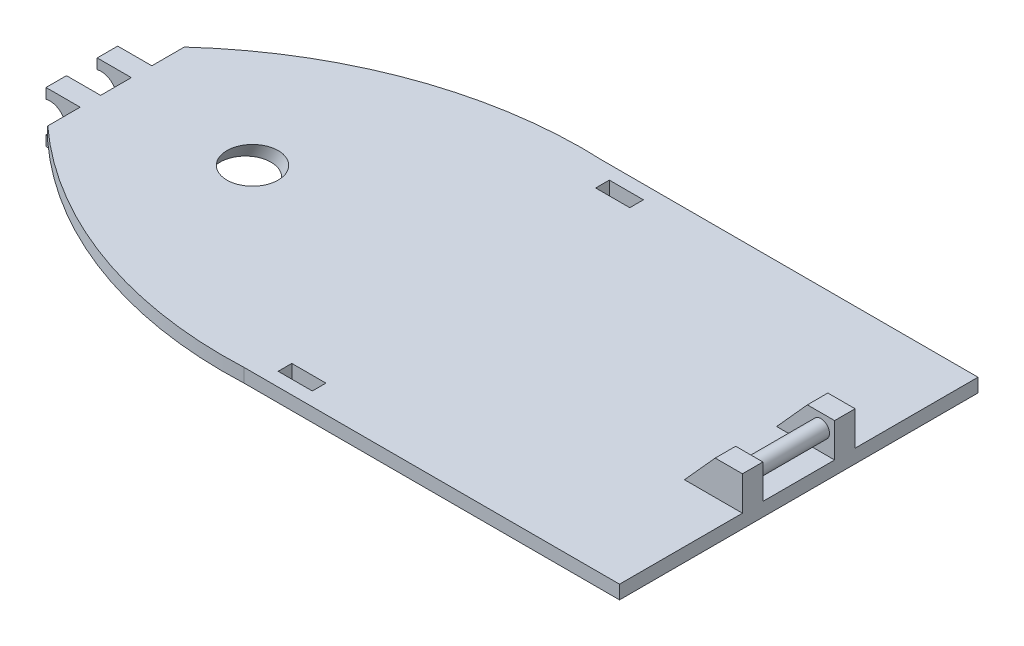
SolidWorks part; units mm, degrees
ref_plane "Front Plane" through (0, 0, 0) normal (0, 0, 1) x (1, 0, 0)
ref_plane "Top Plane" through (0, 0, 0) normal (0, 1, 0) x (1, 0, 0)
ref_plane "Right Plane" through (0, 0, 0) normal (1, 0, 0) x (0, 0, -1)
sketch "Sketch1" plane through (0, 0, 0) normal (0, 1, 0) x (1, 0, 0)
  line L0 (-110, 0) -> (0, 0)
  line L1 (0, 0) -> (0, -105)
  line L2 (0, -105) -> (-110, -105)
  line L4 (-200, -72.5) -> (-200, -32.5)
  arc A2 (-200, -32.5) -> (-110, 0) centre (-115.7774, -124.8664) cw
  arc A3 (-200, -72.5) -> (-110, -105) centre (-115.7774, 19.8664) ccw
  point P11 (-200, -52.5)
  point P12 (0, -52.5)
  dimension "D4" = 40
  dimension "D6" = 125
  dimension "D7" = 125
  dimension "D1" = 110
  dimension "D2" = 105
  dimension "D3" = 200
  dimension "D5" = 110
extrude "Boss-Extrude1" add sketch "Sketch1" along normal blind 4
sketch "Sketch2" plane through (0, 0, 105) normal (0, 0, 1) x (1, 0, 0)
  line L0 (-200, 4) -> (-210, 4)
  line L1 (-188, 0) -> (-200, -11)
  line L2 (57.8969, 0) -> (-57.8969, 0) construction
  line L3 (-200, -11) -> (-210, -11)
  line L4 (-210, 4) -> (-210, 1)
  line L5 (-210, -11) -> (-210, -8)
  line L6 (-200, 4) -> (-188, 0)
  arc A0 (-210, 1) -> (-210, -8) centre (-208.8457, -3.5) cw
  point P11 (-204.2, -3.5)
  dimension "D8" = 4.6457
  dimension "D1" = 10
  dimension "D2" = 15
  dimension "D3" = 3
  dimension "D4" = 3
  dimension "D5" = 10
  dimension "D6" = 5.8
  dimension "D7" = 22
extrude "Boss-Extrude2" add sketch "Sketch2" along normal mid plane 6 from offset 45 offset against normal yes
ref_plane "Plane1" through (0, 0, 52.5) normal (0, 0, 1) x (1, 0, 0)
mirror "Mirror1" about plane through (0, 0, 52.5) normal (0, 0, 1) of "Boss-Extrude2"
ref_plane "Plane2" through (-100, 0, 0) normal (1, 0, 0) x (0, 0, -1)
sketch "Sketch5" plane through (0, 0, 105) normal (0, 0, 1) x (1, 0, 0)
  line L0 (-16.9798, 4) -> (-7.9798, 14)
  line L1 (-110, 4) -> (0, 4) construction
  line L2 (-7.9798, 14) -> (0, 14)
  line L3 (0, 14) -> (0, 4)
  line L4 (0, 4) -> (-16.9798, 4)
  dimension "D1" = 10
  dimension "D2" = 9
extrude "Boss-Extrude3" add sketch "Sketch5" along direction (0, 0, 1) on the side against the normal mid plane 6 from offset 39 contours L2 L3 L4 L0 offset against normal yes
mirror "Mirror4" about plane through (0, 0, 52.5) normal (0, 0, 1) of "Boss-Extrude3"
sketch "Sketch6" plane through (0, 0, 42) normal (0, 0, 1) x (1, 0, 0)
  line L0 (0, -13.75) -> (0, 13.75) construction
  line L1 (-110, 4) -> (0, 4) construction
  circle A0 centre (-4, 10) radius 2.5
  dimension "D1" = 5
  dimension "D2" = 4
  dimension "D3" = 6
extrude "Boss-Extrude4" add sketch "Sketch6" along normal up to body separate body
sketch "Sketch7" plane through (0, 4, 0) normal (0, 1, 0) x (1, 0, 0)
  line L0 (-110, -105) -> (0, -105) construction
  line L1 (-104, -101) -> (-94, -101)
  line L2 (-104, -101) -> (-104, -97)
  line L3 (-104, -97) -> (-94, -97)
  line L4 (-94, -101) -> (-94, -97)
  dimension "D1" = 6
  dimension "D2" = 10
  dimension "D3" = 4
  dimension "D4" = 4
extrude "Cut-Extrude1" cut sketch "Sketch7" against normal blind 10
mirror "Mirror5" about plane through (0, 0, 52.5) normal (0, 0, 1) of "Cut-Extrude1"
sketch "Sketch8" plane through (0, 4, 0) normal (0, 1, 0) x (1, 0, 0)
  line L0 (-13.75, -52.5) -> (13.75, -52.5) construction
  line L1 (-200, -48) -> (-200, -57) construction
  circle A0 centre (-160, -52.5) radius 7.5
  dimension "D2" = 15
  dimension "D1" = 40
sketch "Sketch9" plane through (0, 0, 52.5) normal (0, 0, 1) x (1, 0, 0)
  line L0 (-160, 4) -> (-163.8674, -3.4662)
  line L1 (-152.5, 4) -> (-167.5, 4) construction
sweep "Cut-Sweep1" cut profiles "Sketch8" path "Sketch9"
